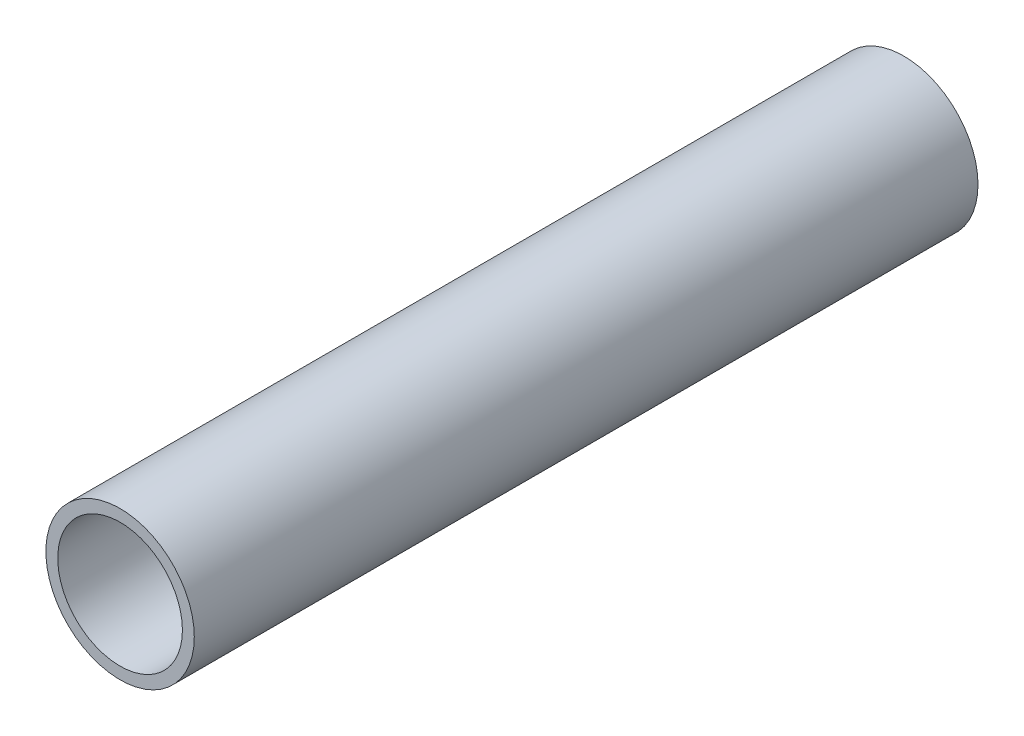
SolidWorks part; units mm, degrees
ref_plane "Alzado" through (0, 0, 0) normal (0, 0, 1) x (1, 0, 0)
ref_plane "Planta" through (0, 0, 0) normal (0, 1, 0) x (1, 0, 0)
ref_plane "Vista lateral" through (0, 0, 0) normal (1, 0, 0) x (0, 0, -1)
sketch "Croquis1" plane through (0, 0, 0) normal (0, 0, 1) x (1, 0, 0)
  circle A0 centre (0, 0) radius 12.5
  circle A1 centre (0, 0) radius 10.5
  dimension "D1" = 25
  dimension "D2" = 2
extrude "Saliente-Extruir1" add sketch "Croquis1" along normal blind 132
